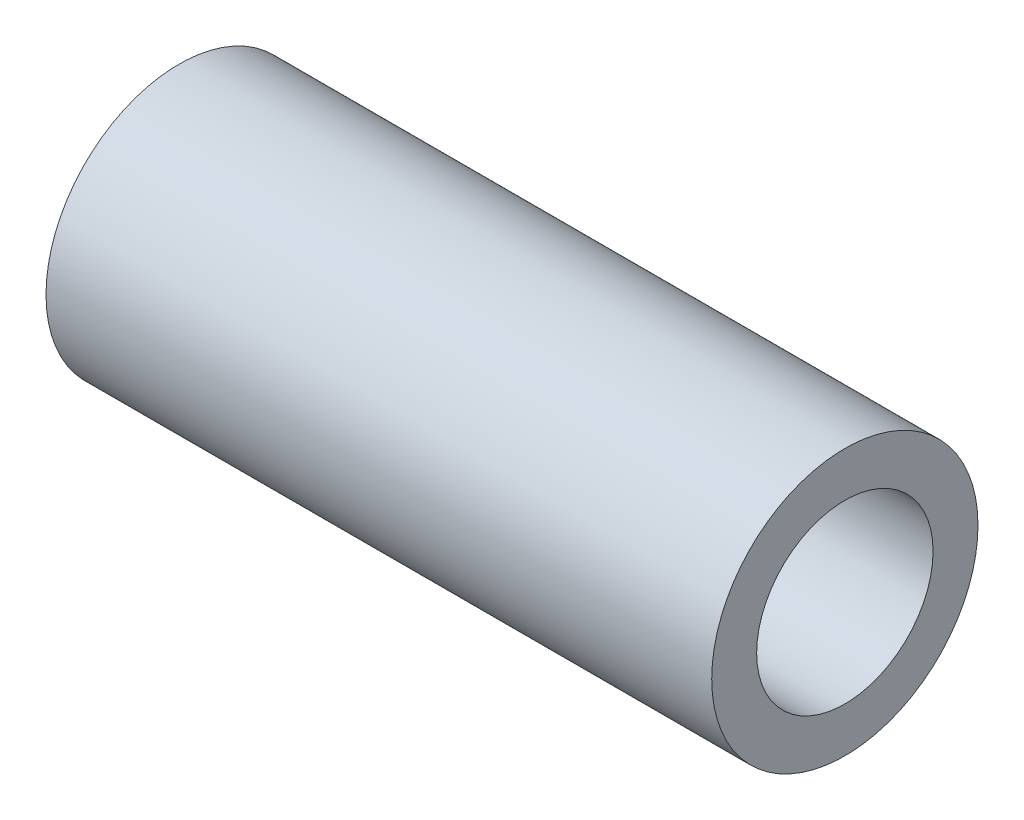
SolidWorks part; units mm, degrees
ref_plane "Front Plane" through (0, 0, 0) normal (0, 0, 1) x (1, 0, 0)
ref_plane "Top Plane" through (0, 0, 0) normal (0, 1, 0) x (1, 0, 0)
ref_plane "Right Plane" through (0, 0, 0) normal (1, 0, 0) x (0, 0, -1)
sketch "Sketch1" plane through (0, 0, 0) normal (1, 0, 0) x (0, 0, -1)
  circle A0 centre (0, 0) radius 2.65
  circle A1 centre (0, 0) radius 4
  dimension "D1" = 5.3
  dimension "D2" = 8
extrude "Boss-Extrude1" add sketch "Sketch1" along normal blind 20
